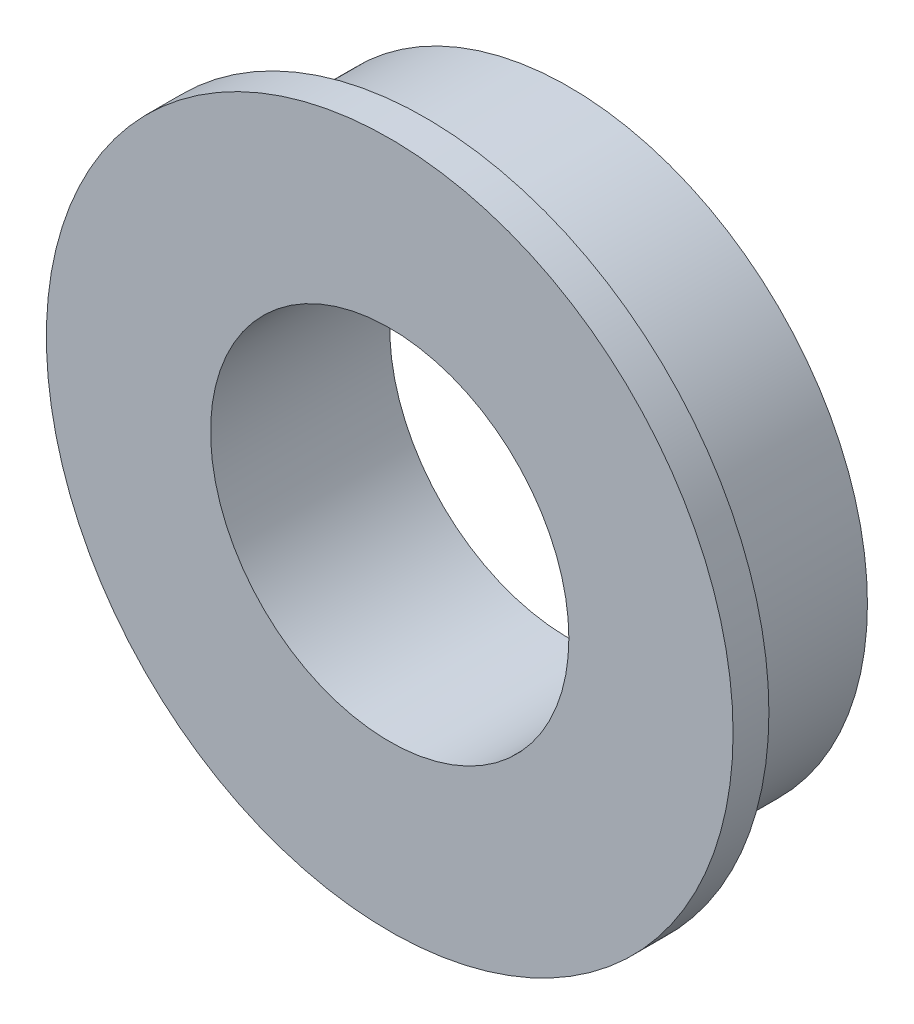
SolidWorks part; units mm, degrees
material "ｽﾃﾝﾚｽ鋼(ｸﾛﾑ)"
ref_plane "正面" through (0, 0, 0) normal (0, 0, 1) x (1, 0, 0)
ref_plane "平面" through (0, 0, 0) normal (0, 1, 0) x (1, 0, 0)
ref_plane "右側面" through (0, 0, 0) normal (1, 0, 0) x (0, 0, -1)
sketch "ｽｹｯﾁ1" plane through (0, 0, 0) normal (1, 0, 0) x (0, 0, -1)
  line L0 (0, 0) -> (50000, 0) construction
  line L1 (0, 0) -> (0, 50000) construction
  line L2 (-0.6, 5.75) -> (-0.6, 3)
  line L3 (-0.6, 3) -> (2.4, 3)
  line L4 (2.4, 3) -> (2.4, 5)
  line L5 (2.4, 5) -> (0, 5)
  line L6 (0, 5) -> (0, 5.75)
  line L7 (0, 5.75) -> (-0.6, 5.75)
  dimension "D1" = 6
  dimension "D2" = 10
  dimension "D3" = 0.6
  dimension "D4" = 3
  dimension "D5" = 11.5
revolve "回転1" add sketch "ｽｹｯﾁ1" angle 360 about L0
